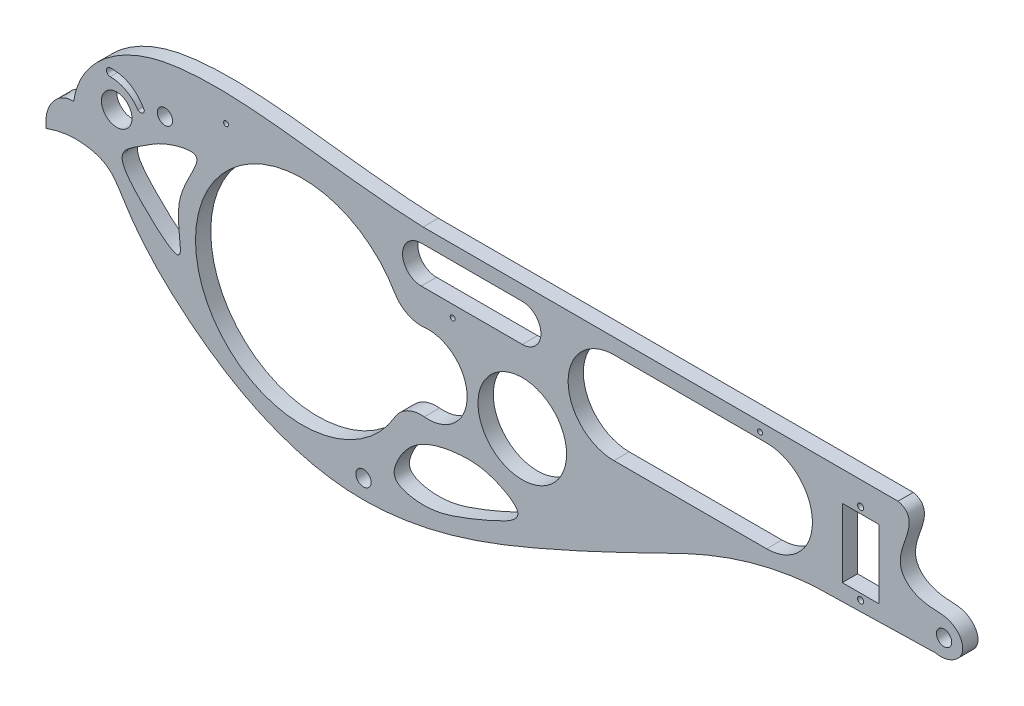
SolidWorks part; units mm, degrees
ref_plane "Front Plane" through (0, 0, 0) normal (0, 0, 1) x (1, 0, 0)
ref_plane "Top Plane" through (0, 0, 0) normal (0, 1, 0) x (1, 0, 0)
ref_plane "Right Plane" through (0, 0, 0) normal (1, 0, 0) x (0, 0, -1)
sketch "Sketch3" plane through (0, 0, 0) normal (0, 0, 1) x (1, 0, 0)
  line L0 (6.7959, 101.4395) -> (306.7959, 101.4395) construction
  line L1 (130.2022, 133.6481) -> (285.7114, 133.6481)
  line L2 (298.1944, 96.7692) -> (258.822, 95.8373)
  line L3 (131.906, 92.7019) -> (162.706, 92.7019) construction
  line L4 (129.6002, 122.7019) -> (162.706, 122.7019) construction
  line L5 (67.5559, 92.7019) -> (131.906, 92.7019) construction
  line L6 (129.6002, 128.8003) -> (162.706, 128.8003)
  line L7 (129.6002, 116.6034) -> (162.706, 116.6034)
  line L8 (192.706, 113.6481) -> (242.706, 113.6481) construction
  line L9 (192.706, 128.6481) -> (242.706, 128.6481)
  line L10 (192.706, 98.6481) -> (242.706, 98.6481)
  line L12 (267.4715, 123.9395) -> (279.4715, 123.9395)
  line L13 (267.4715, 123.9395) -> (267.4715, 101.4395)
  line L14 (267.4715, 101.4395) -> (279.4715, 101.4395)
  line L15 (279.4715, 123.9395) -> (279.4715, 101.4395)
  line L16 (267.4715, 123.9395) -> (279.4715, 101.4395) construction
  line L17 (267.4715, 101.4395) -> (279.4715, 123.9395) construction
  circle A0 centre (29.9168, 116.7757) radius 5
  arc A2 (120.957, 110.3052) -> (120.957, 75.0986) centre (90.706, 92.7019) ccw
  arc A3 (130.6137, 80.0176) -> (130.6137, 105.3862) centre (131.906, 92.7019) ccw
  arc A4 (130.6137, 80.0176) -> (120.957, 75.0986) centre (129.6002, 70.069) ccw
  arc A5 (130.6137, 105.3862) -> (120.957, 110.3052) centre (129.6002, 115.3347) cw
  circle A6 centre (162.706, 92.7019) radius 14.5
  circle A7 centre (45.706, 122.7019) radius 2.5
  circle A8 centre (110.706, 52.7019) radius 2.5
  circle A9 centre (139.906, 112.7019) radius 0.8
  circle A10 centre (65.706, 130.7019) radius 0.8
  circle A11 centre (240.5337, 130.7019) radius 0.8
  arc A12 (129.6002, 128.8003) -> (129.6002, 116.6034) centre (129.6002, 122.7019) ccw
  arc A13 (162.706, 116.6034) -> (162.706, 128.8003) centre (162.706, 122.7019) ccw
  arc A14 (27.8066, 127.5837) -> (27.8066, 125.0837) centre (27.8066, 126.3337) ccw
  arc A15 (36.8498, 120.1829) -> (38.958, 121.0918) centre (37.708, 121.0918) ccw
  arc A16 (192.706, 128.6481) -> (192.706, 98.6481) centre (192.706, 113.6481) ccw
  arc A17 (242.706, 98.6481) -> (242.706, 128.6481) centre (242.706, 113.6481) ccw
  circle A18 centre (273.4715, 99.4395) radius 1
  circle A19 centre (273.4715, 125.9395) radius 1
  circle A20 centre (300.7959, 102.4395) radius 2.5
  spline S0 degree 3 poles (6.7959, 101.4395) (6.3442, 106.4769) (10.4893, 112.3015) (15.8234, 112.0735) knots 0 0 0 0 1 1 1 1
  spline S1 degree 3 poles (15.8234, 112.0735) (17.737, 124.9406) (32.6369, 136.2233) (57.7953, 140.1186) (87.9987, 138.4546) (113.3983, 134.2375) (130.2022, 133.6481) knots 0 0 0 0 0.288569 0.388427 0.602707 1 1 1 1
  spline S2 degree 3 poles (285.7114, 133.6481) (290.3092, 132.6141) (289.2734, 126.5473) (286.7081, 120.4845) (286.0868, 115.3726) (289.4465, 110.5224) (295.757, 108.5401) (302.9008, 109.1289) (306.9385, 104.8706) (306.9653, 98.4992) (301.2996, 95.8368) (298.1944, 96.7692) knots 0 0 0 0 0.169883 0.267905 0.359102 0.418588 0.56072 0.679524 0.781874 0.818154 1 1 1 1
  spline S3 degree 3 poles (258.822, 95.8373) (247.0173, 95.1037) (230.334, 90.7183) (209.4442, 80.9092) (192.7052, 72.5069) (167.703, 61.11) (138.4359, 48.8711) (104.8039, 44.7911) (75.9674, 52.8776) (51.2832, 69.2804) (37.1923, 83.9745) (31.9554, 92.7019) knots 0 0 0 0 0.140252 0.203194 0.274778 0.363372 0.530716 0.651093 0.758817 0.879982 1 1 1 1
  spline S4 degree 1 poles (6.7959, 101.4395) (6.7959, 99.8852) knots 0 0 1 1
  spline S5 degree 3 poles (6.7959, 99.8852) (11.1597, 101.5228) (18.1517, 102.517) (27.7919, 99.5136) (30.5807, 94.935) (31.9554, 92.7019) knots 0 0 0 0 0.481673 0.718975 1 1 1 1
  spline S6 degree 3 poles (119.2781, 56.8819) (122.7361, 66.0932) (129.5527, 73.0769) (142.4433, 75.6665) (152.6615, 74.9693) (165.094, 67.4911) (151.767, 61.0753) (141.894, 57.1104) (131.1059, 53.6264) (119.2781, 56.8819) (122.7361, 66.0932) (129.5527, 73.0769) knots -0.29666 -0.141672 -0.06146 0 0.113321 0.252345 0.383345 0.473297 0.574796 0.70334 0.858328 0.93854 1 1.113321 1.252345 1.383345 only from (122.2092, 63.92) to (122.2092, 63.92)
  spline S7 degree 2 poles (27.8066, 127.5837) (35.2664, 127.7837) (38.958, 121.0918) knots 0 0 0 1 1 1
  spline S8 degree 2 poles (27.8066, 125.0837) (33.5176, 124.9054) (36.8498, 120.1829) knots 0 0 0 1 1 1
  spline S9 degree 3 poles (44.7276, 115.2676) (61.7967, 119.6008) (46.2218, 102.1001) (54.7557, 78.9561) (37.8034, 94.1157) (28.9082, 105.048) (38.7725, 110.7994) (44.7276, 115.2676) (61.7967, 119.6008) (46.2218, 102.1001) knots -0.311455 -0.223643 -0.116391 0 0.187259 0.369367 0.564057 0.688545 0.776357 0.883609 1 1.187259 1.369367 1.564057 only from (55.5691, 116.7757) to (55.5691, 116.7757)
  point P37 (258.822, 133.6481)
  point P41 (100.706, 92.7019)
  point P55 (45.706, 122.7019)
  point P58 (110.706, 52.7019)
  point P61 (139.906, 112.7019)
  point P64 (65.706, 130.7019)
  point P67 (240.5337, 130.7019)
  point P72 (146.1531, 122.7019)
  point P95 (217.706, 113.6481)
  point P108 (273.4715, 112.6895)
  point P113 (273.4715, 125.9395)
  point P114 (273.4715, 99.4395)
  dimension "D3" = 10
  dimension "D4" = 10
  dimension "D7" = 10
  dimension "D8" = 45
  dimension "D10" = 5
  dimension "D13" = 5
  dimension "D16" = 1.6
  dimension "D19" = 35
  dimension "D21" = 2.5
  dimension "D22" = 2.5
  dimension "D33" = 2
  dimension "D34" = 2
  dimension "D35" = 5
  dimension "D1" = 300
  dimension "D2" = 155.5091
  dimension "D5" = 41.2
  dimension "D6" = 30.8
  dimension "D9" = 30
  dimension "D11" = 40
  dimension "D12" = 20
  dimension "D14" = 8
  dimension "D15" = 20
  dimension "D17" = 8
  dimension "D18" = 20
  dimension "D20" = 0
  dimension "D23" = 50
  dimension "D24" = 30
  dimension "D25" = 20
  dimension "D26" = 30
  dimension "D27" = 12
  dimension "D28" = 22.5
  dimension "D29" = 2
  dimension "D30" = 2
  dimension "D31" = 6
  dimension "D32" = 6
  dimension "D36" = 6
  dimension "D37" = 1
extrude "Boss-Extrude1" add sketch "Sketch3" along normal blind 5
ref_plane "Plane1" through (0, 0, 2.5) normal (0, 0, 1) x (1, 0, 0)
